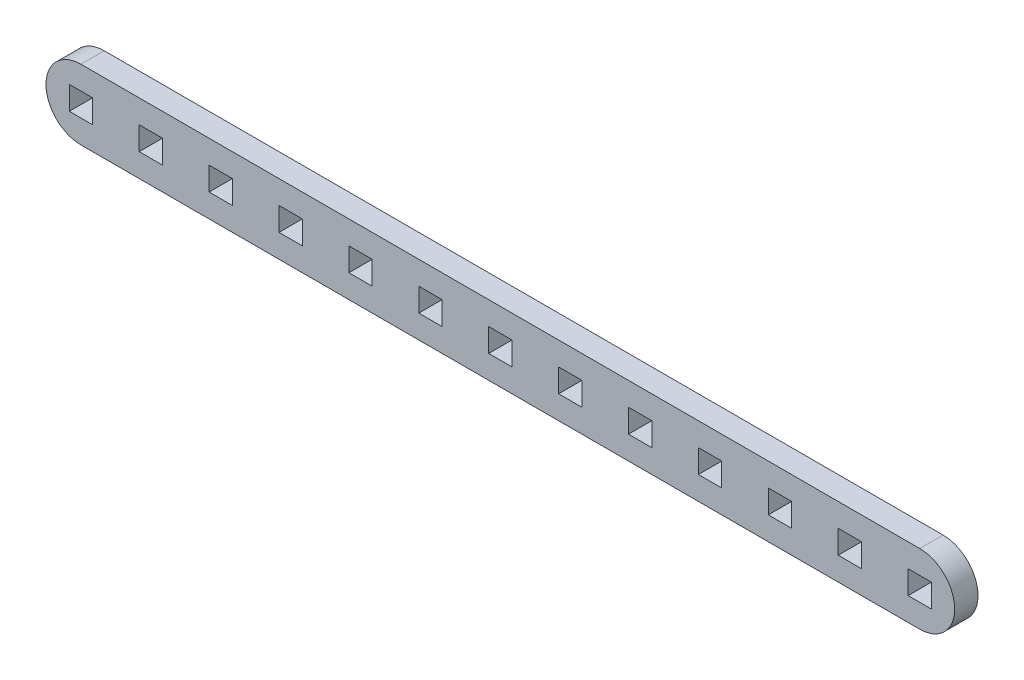
SolidWorks part; units mm, degrees
ref_plane "Alzado" through (0, 0, 0) normal (0, 0, 1) x (1, 0, 0)
ref_plane "Planta" through (0, 0, 0) normal (0, 1, 0) x (1, 0, 0)
ref_plane "Vista lateral" through (0, 0, 0) normal (1, 0, 0) x (0, 0, -1)
sketch "Model" plane through (0, 0, 0) normal (0, 0, 1) x (1, 0, 0)
  line L0 (8.4048, 293.775) -> (8.4048, 290.775)
  line L1 (11.4048, 293.775) -> (8.4048, 293.775)
  line L2 (11.4048, 290.775) -> (11.4048, 293.775)
  line L3 (8.4048, 290.775) -> (11.4048, 290.775)
  line L4 (17.4048, 293.775) -> (17.4048, 290.775)
  line L5 (20.4048, 293.775) -> (17.4048, 293.775)
  line L6 (20.4048, 290.775) -> (20.4048, 293.775)
  line L7 (17.4048, 290.775) -> (20.4048, 290.775)
  line L8 (26.4048, 293.775) -> (26.4048, 290.775)
  line L9 (29.4048, 293.775) -> (26.4048, 293.775)
  line L10 (29.4048, 290.775) -> (29.4048, 293.775)
  line L11 (26.4048, 290.775) -> (29.4048, 290.775)
  line L12 (35.4048, 293.775) -> (35.4048, 290.775)
  line L13 (38.4048, 293.775) -> (35.4048, 293.775)
  line L14 (38.4048, 290.775) -> (38.4048, 293.775)
  line L15 (35.4048, 290.775) -> (38.4048, 290.775)
  line L16 (44.4048, 293.775) -> (44.4048, 290.775)
  line L17 (47.4048, 293.775) -> (44.4048, 293.775)
  line L18 (47.4048, 290.775) -> (47.4048, 293.775)
  line L19 (44.4048, 290.775) -> (47.4048, 290.775)
  line L20 (53.4048, 293.775) -> (53.4048, 290.775)
  line L21 (56.4048, 293.775) -> (53.4048, 293.775)
  line L22 (56.4048, 290.775) -> (56.4048, 293.775)
  line L23 (53.4048, 290.775) -> (56.4048, 290.775)
  line L24 (62.4048, 293.775) -> (62.4048, 290.775)
  line L25 (65.4048, 293.775) -> (62.4048, 293.775)
  line L26 (65.4048, 290.775) -> (65.4048, 293.775)
  line L27 (62.4048, 290.775) -> (65.4048, 290.775)
  line L28 (71.4048, 293.775) -> (71.4048, 290.775)
  line L29 (74.4048, 293.775) -> (71.4048, 293.775)
  line L30 (74.4048, 290.775) -> (74.4048, 293.775)
  line L31 (71.4048, 290.775) -> (74.4048, 290.775)
  line L32 (80.4048, 293.775) -> (80.4048, 290.775)
  line L33 (83.4048, 293.775) -> (80.4048, 293.775)
  line L34 (83.4048, 290.775) -> (83.4048, 293.775)
  line L35 (80.4048, 290.775) -> (83.4048, 290.775)
  line L36 (89.4048, 293.775) -> (89.4048, 290.775)
  line L37 (92.4048, 293.775) -> (89.4048, 293.775)
  line L38 (92.4048, 290.775) -> (92.4048, 293.775)
  line L39 (89.4048, 290.775) -> (92.4048, 290.775)
  line L40 (116.4048, 293.775) -> (116.4048, 290.775)
  line L41 (119.4048, 293.775) -> (116.4048, 293.775)
  line L42 (119.4048, 290.775) -> (119.4048, 293.775)
  line L43 (116.4048, 290.775) -> (119.4048, 290.775)
  line L44 (98.4048, 293.775) -> (98.4048, 290.775)
  line L45 (101.4048, 293.775) -> (98.4048, 293.775)
  line L46 (101.4048, 290.775) -> (101.4048, 293.775)
  line L47 (98.4048, 290.775) -> (101.4048, 290.775)
  line L48 (107.4048, 293.775) -> (107.4048, 290.775)
  line L49 (110.4048, 293.775) -> (107.4048, 293.775)
  line L50 (110.4048, 290.775) -> (110.4048, 293.775)
  line L51 (107.4048, 290.775) -> (110.4048, 290.775)
  line L52 (9.9048, 296.775) -> (117.9048, 296.775)
  line L53 (9.9048, 287.775) -> (117.9048, 287.775)
  arc A0 (9.9048, 296.775) -> (9.9048, 287.775) centre (9.9048, 292.275) ccw
  arc A1 (117.9048, 287.775) -> (117.9048, 296.775) centre (117.9048, 292.275) ccw
extrude "Saliente-Extruir1" add sketch "Model" along normal blind 3
